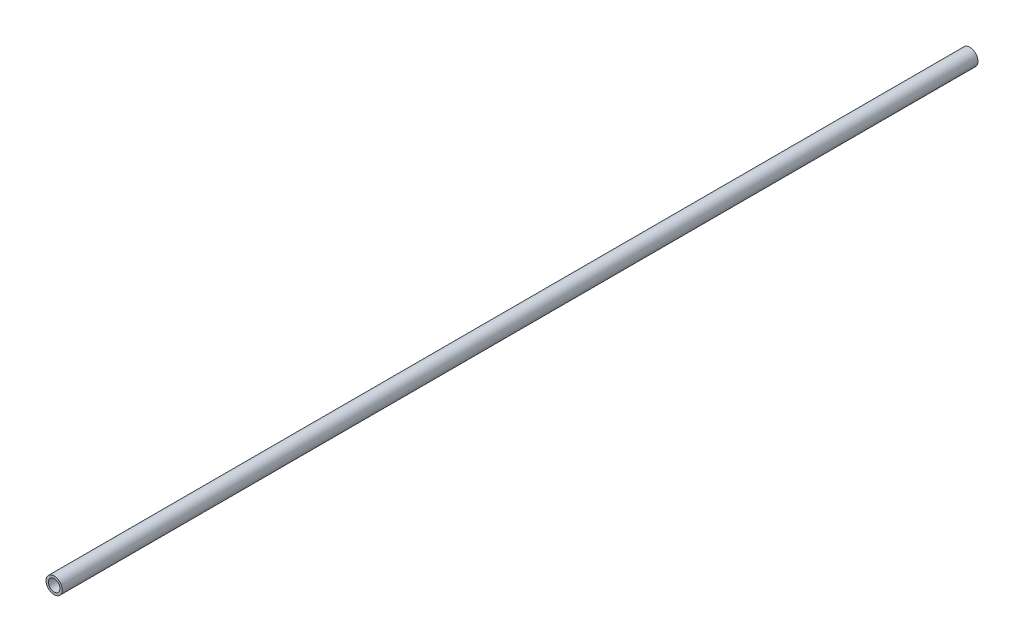
SolidWorks part; units mm, degrees
material "Thornel Mat VMA"
ref_plane "Front Plane" through (0, 0, 0) normal (0, 0, 1) x (1, 0, 0)
ref_plane "Top Plane" through (0, 0, 0) normal (0, 1, 0) x (1, 0, 0)
ref_plane "Right Plane" through (0, 0, 0) normal (1, 0, 0) x (0, 0, -1)
sketch "Sketch1" plane through (0, 0, 0) normal (0, 0, 1) x (1, 0, 0)
  circle A0 centre (0, 6.4558) radius 4.4704
  circle A1 centre (0, 6.4558) radius 3.175
  dimension "D1" = 6.35
  dimension "D2" = 8.9408
extrude "Boss-Extrude1" add sketch "Sketch1" along normal blind 502.539
